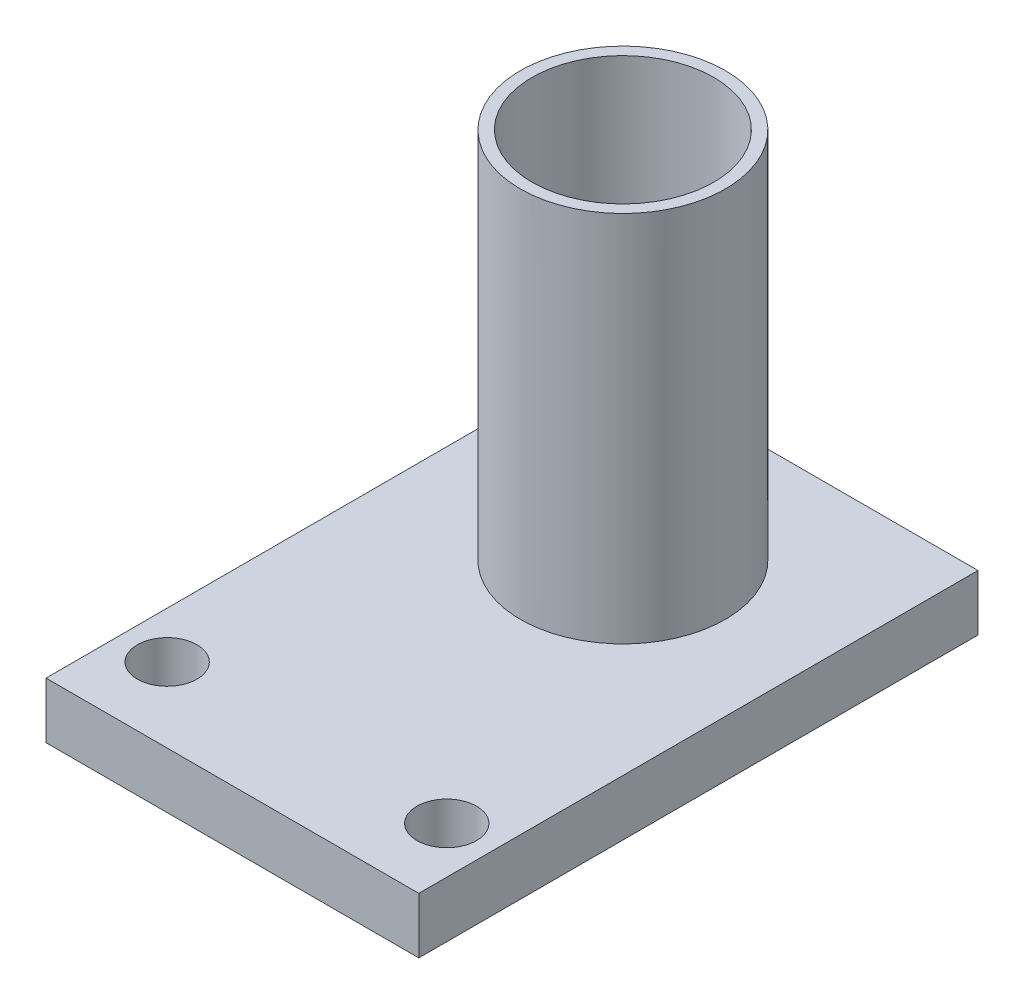
SolidWorks part; units mm, degrees
ref_plane "Front" through (0, 0, 0) normal (0, 0, 1) x (1, 0, 0)
ref_plane "Top" through (0, 0, 0) normal (0, 1, 0) x (1, 0, 0)
ref_plane "Right" through (0, 0, 0) normal (1, 0, 0) x (0, 0, -1)
sketch "Sketch1" plane through (0, 0, 0) normal (0, 1, 0) x (1, 0, 0)
  line L1 (-10, -15) -> (10, -15)
  line L2 (-10, -15) -> (-10, 15)
  line L3 (-10, 15) -> (10, 15)
  line L4 (10, -15) -> (10, 15)
  line L5 (-10, -15) -> (10, 15) construction
  line L6 (-10, 15) -> (10, -15) construction
  point P0 (0, 0)
  dimension "D1" = 20
  dimension "D2" = 30
extrude "Boss-Extrude1" add sketch "Sketch1" along normal blind 3
sketch "Sketch2" plane through (0, 3, 0) normal (0, 1, 0) x (1, 0, 0)
  line L0 (-10, 15) -> (-10, -15) construction
  line L1 (10, -15) -> (-10, -15)
  line L2 (10, -15) -> (10, -7)
  line L3 (10, -7) -> (-10, -7)
  line L4 (-10, -15) -> (-10, -7)
  line L5 (-7.5, -7) -> (-7.5, -15) construction
  line L6 (7.5, -7) -> (7.5, -15) construction
  point P11 (-7.5, -11)
  point P12 (7.5, -11)
  dimension "D1" = 8
  dimension "D2" = 2.5
  dimension "D3" = 2.5
hole_wizard "M3 Clearance Hole1" positions "3DSketch1" profile "Sketch3" hole size "M3" standard "ANSI Metric"
sketch3d "3DSketch1"
  point P0 (-7.5, 3, 11)
  point P3 (7.5, 3, 11)
sketch "Sketch3" plane through (-7.5, 3, 11) normal (1, 0, 0) x (0, 0, 1)
  line L0 (0, 0) -> (0, 5.9614)
  line L1 (0, 5.9614) -> (1.6, 5)
  line L2 (1.6, 5) -> (1.6, 0)
  line L5 (1.6, 0) -> (0, 0)
  line L10 (0, 5.9614) -> (-1.6, 5) construction
  line L11 (0, -6.35) -> (0, 107.95) construction
  dimension "Hole Dia." = 3.2
  dimension "Hole Depth" = 5
  dimension "Drill Angle" = 118
sketch "Sketch4" plane through (0, 3, 0) normal (0, 1, 0) x (1, 0, 0)
  line L0 (0, -15) -> (0, 5.95) construction
  line L1 (10, -15) -> (-10, -15) construction
  circle A0 centre (0, 5.95) radius 4.875
  dimension "D2" = 9.75
  dimension "D1" = 20.95
extrude "Cut-Extrude1" cut sketch "Sketch4" against normal up to surface (3 mm away) up to face at (-7.5, 0, 9.4)
sketch "Sketch5" plane through (0, 3, 0) normal (0, 1, 0) x (1, 0, 0)
  circle A0 centre (0, 5.95) radius 5.5
  circle A1 centre (0, 5.95) radius 4.875
  dimension "D1" = 11
  dimension "D2" = 9.75
extrude "Boss-Extrude2" add sketch "Sketch5" along normal blind 20
